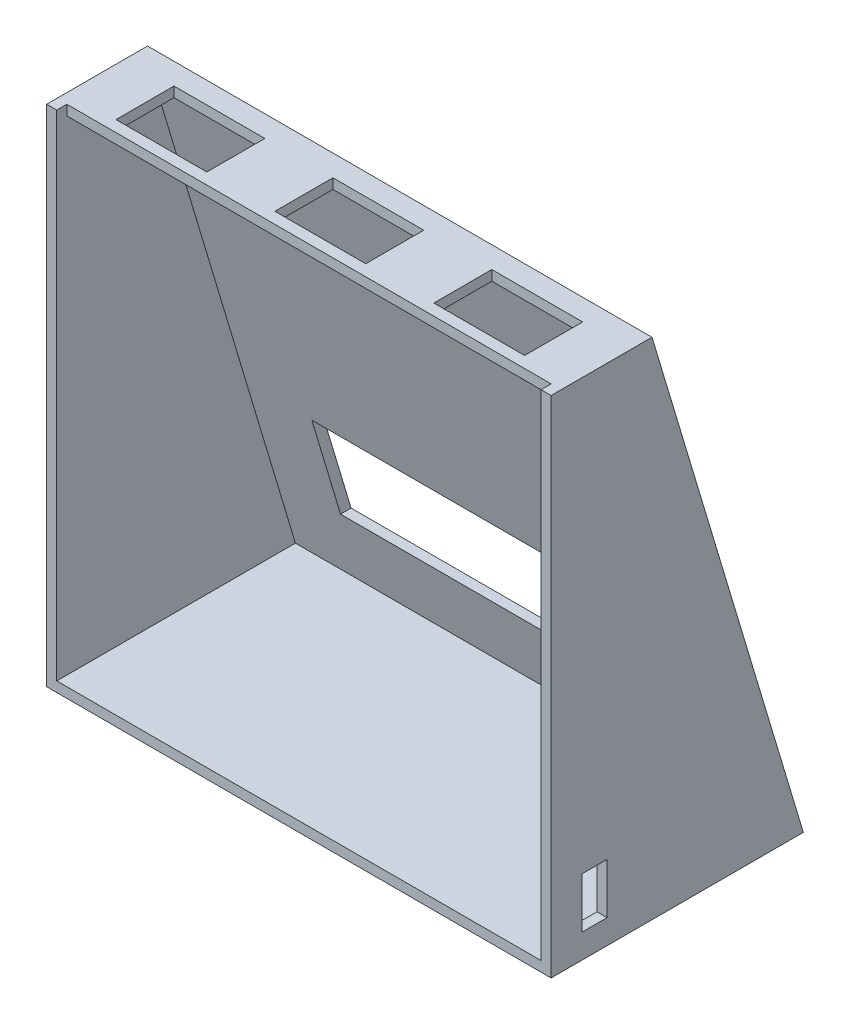
SolidWorks part; units mm, degrees
ref_plane "Front Plane" through (0, 0, 0) normal (0, 0, 1) x (1, 0, 0)
ref_plane "Top Plane" through (0, 0, 0) normal (0, 1, 0) x (1, 0, 0)
ref_plane "Right Plane" through (0, 0, 0) normal (1, 0, 0) x (0, 0, -1)
sketch "Sketch1" plane through (0, 0, 0) normal (1, 0, 0) x (0, 0, -1)
  line L0 (-46.5656, -45.8054) -> (3.4344, -45.8054)
  line L1 (3.4344, -45.8054) -> (-26.5656, 54.1946)
  line L2 (-26.5656, 54.1946) -> (-46.5656, 54.1946)
  line L3 (-46.5656, 54.1946) -> (-46.5656, -45.8054)
  dimension "D1" = 100
  dimension "D2" = 20
  dimension "D3" = 50
extrude "Boss-Extrude1" add sketch "Sketch1" along normal blind 2
sketch "Sketch2" plane through (2, 0, 0) normal (1, 0, 0) x (0, 0, -1)
  line L1 (-26.5656, 54.1946) -> (3.4344, -45.8054)
  line L2 (3.4344, -45.8054) -> (-44.5656, -45.8054)
  line L5 (-44.5656, -43.8054) -> (0.7463, -43.8054)
  line L6 (-28.0537, 52.1946) -> (0.7463, -43.8054)
  line L12 (-44.5656, 54.1946) -> (-26.5656, 54.1946)
  line L13 (-44.5656, 54.1946) -> (-44.5656, 52.1946)
  line L14 (-44.5656, 52.1946) -> (-28.0537, 52.1946)
  line L15 (-44.5656, -43.8054) -> (-46.5656, -43.8054)
  line L16 (-46.5656, 54.1946) -> (-46.5656, -45.8054) construction
  line L17 (-46.5656, -43.8054) -> (-46.5656, -45.8054)
  line L18 (-46.5656, -45.8054) -> (-44.5656, -45.8054)
  dimension "D1" = 2
  dimension "D2" = 2
  dimension "D3" = 2
extrude "Boss-Extrude2" add sketch "Sketch2" along normal blind 96
sketch "Sketch3" plane through (98, 0, 0) normal (1, 0, 0) x (0, 0, -1)
  line L5 (-46.5656, 54.1946) -> (-26.5656, 54.1946)
  line L6 (-26.5656, 54.1946) -> (3.4344, -45.8054)
  line L7 (3.4344, -45.8054) -> (-46.5656, -45.8054)
  line L8 (-46.5656, -45.8054) -> (-46.5656, 54.1946)
extrude "Boss-Extrude3" add sketch "Sketch3" along normal blind 2
sketch "Sketch4" plane through (0, 54.1946, 0) normal (0, 1, 0) x (1, 0, 0)
  line L0 (-4.3465, -36.5656) -> (110.5728, -36.5656) construction
  line L1 (100, -26.5656) -> (0, -26.5656) construction
  line L2 (50, -30.8156) -> (59, -30.8156)
  line L3 (50, 14.0021) -> (50, -60.1017) construction
  line L4 (0, -26.5656) -> (0, -46.5656) construction
  line L5 (59, -30.8156) -> (59, -36.5656)
  line L7 (59, -42.3156) -> (41, -42.3156)
  line L8 (41, -42.3156) -> (41, -30.8156)
  line L9 (41, -30.8156) -> (50, -30.8156)
  line L10 (59, -36.5656) -> (59, -42.3156)
  line L11 (72.5, -30.8156) -> (72.5, -42.3156)
  line L12 (72.5, 14.0021) -> (72.5, -61.5859) construction
  line L13 (72.5, -42.3156) -> (90.5, -42.3156)
  line L14 (90.5, -42.3156) -> (90.5, -36.5656)
  line L15 (90.5, -36.5656) -> (90.5, -30.8156)
  line L16 (90.5, -30.8156) -> (72.5, -30.8156)
  line L17 (27.5, -30.8156) -> (27.5, -42.3156)
  line L18 (27.5, -42.3156) -> (9.5, -42.3156)
  line L19 (9.5, -42.3156) -> (9.5, -36.5656)
  line L20 (9.5, -36.5656) -> (9.5, -30.8156)
  line L21 (9.5, -30.8156) -> (27.5, -30.8156)
  dimension "D1" = 10
  dimension "D2" = 50
  dimension "D3" = 9
  dimension "D4" = 9
  dimension "D5" = 11.5
  dimension "D6" = 13.5
  dimension "D7" = 18
extrude "Cut-Extrude1" cut sketch "Sketch4" against normal blind 2
sketch "Sketch5" plane through (0, 0, 0) normal (0, 0, 1) x (1, 0, 0)
  line L0 (50, 57.1597) -> (50, -51.4088) construction
  line L1 (100, -45.8054) -> (100, 54.1946) construction
  line L2 (115.5185, -20.8054) -> (-11.6504, -20.8054) construction
  line L3 (100, -45.8054) -> (0, -45.8054) construction
  line L4 (85, -11.3054) -> (50, -11.3054)
  line L5 (50, -11.3054) -> (15, -11.3054)
  line L6 (15, -11.3054) -> (15, -20.8054)
  line L7 (15, -20.8054) -> (15, -30.3054)
  line L8 (15, -30.3054) -> (85, -30.3054)
  line L9 (85, -30.3054) -> (85, -11.3054)
  dimension "D1" = 50
  dimension "D2" = 25
  dimension "D3" = 70
  dimension "D4" = 19
extrude "Cut-Extrude2" cut sketch "Sketch5" against normal blind 2 and the other way blind 20
sketch "Sketch6" plane through (100, 0, 0) normal (1, 0, 0) x (0, 0, -1)
  line L0 (-40.4829, -30.9873) -> (-35.4829, -30.9873)
  line L1 (-35.4829, -30.9873) -> (-35.4829, -40.9873)
  line L2 (-35.4829, -40.9873) -> (-40.4829, -40.9873)
  line L3 (-40.4829, -40.9873) -> (-40.4829, -30.9873)
  dimension "D1" = 10
  dimension "D2" = 5
extrude "Cut-Extrude3" cut sketch "Sketch6" against normal blind 2
